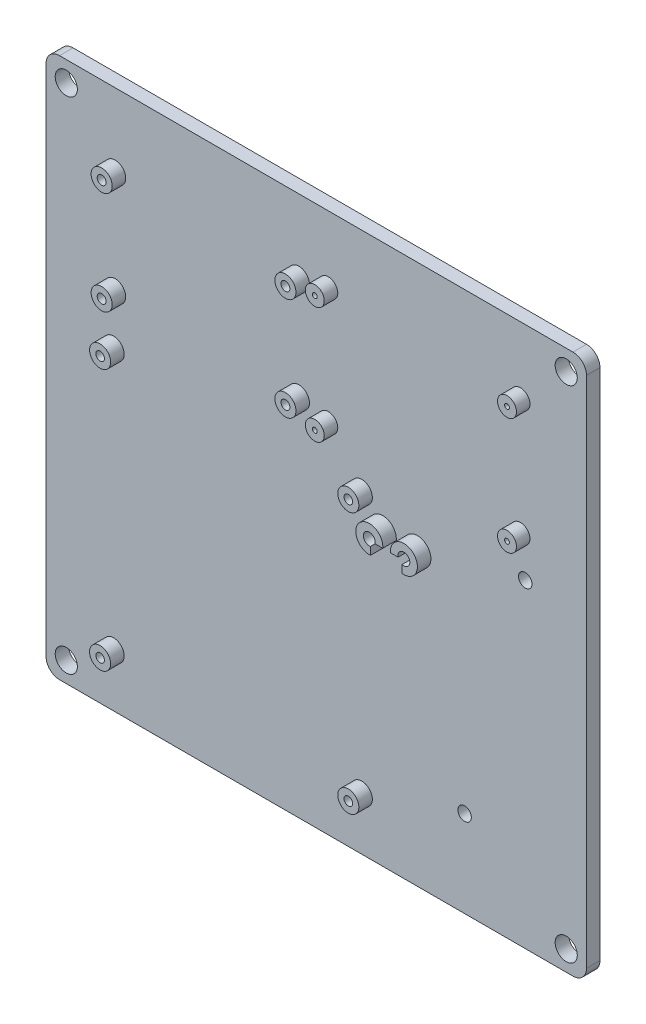
SolidWorks part; units mm, degrees
ref_plane "Alzado" through (0, 0, 0) normal (1, 0, 0) x (0, 1, 0)
ref_plane "Planta" through (0, 0, 0) normal (0, 0, 1) x (0, 1, 0)
ref_plane "Vista lateral" through (0, 0, 0) normal (0, 1, 0) x (-1, 0, 0)
sketch "Croquis1" plane through (0, 0, 0) normal (0, 0, 1) x (0, 1, 0)
  line L1 (-100, -100) -> (100, -100)
  line L2 (-100, -100) -> (-100, 100)
  line L3 (-100, 100) -> (100, 100)
  line L4 (100, -100) -> (100, 100)
  line L5 (-100, -100) -> (100, 100) construction
  line L6 (-100, 100) -> (100, -100) construction
  point P0 (0, 0)
  dimension "D1" = 200
  dimension "D2" = 200
extrude "Saliente-Extruir1" add sketch "Croquis1" along normal blind 5
sketch "Croquis4" plane through (0, 0, 5) normal (0, 0, 1) x (1, 0, 0)
  line L4 (32.4556, 6.9331) -> (36.7578, 6.9331)
  line L5 (36.7578, 6.9331) -> (36.7578, 2.4498)
  line L6 (29.6112, 6.9331) -> (25.086, 6.9331)
  line L7 (25.086, 6.9331) -> (25.086, 2.4245)
  circle A7 centre (4.4664, 32.1842) radius 3.5
  circle A9 centre (4.4664, 32.1842) radius 3.5
  circle A11 centre (4.4664, 32.1842) radius 0.9
  circle A15 centre (4.4664, 32.1842) radius 0.9
  circle A17 centre (75.5865, 75.3643) radius 0.9
  circle A21 centre (75.5865, 75.3643) radius 0.9
  circle A25 centre (75.5865, 75.3643) radius 3.5
  circle A29 centre (75.5865, 75.3643) radius 3.5
  circle A59 centre (-74.9765, 16.2263) radius 1.4
  circle A60 centre (-74.9765, 16.2263) radius 3.9
  circle A61 centre (16.8682, 16.2263) radius 3.9
  circle A62 centre (16.8682, 16.2263) radius 1.4
  circle A63 centre (16.8682, -80.4524) radius 3.9
  circle A64 centre (16.8682, -80.4524) radius 1.4
  circle A65 centre (-74.9765, -80.4524) radius 3.9
  circle A66 centre (-74.9765, -80.4524) radius 1.4
  arc A109 (29.6112, 6.9331) -> (25.086, 2.4245) centre (24.6334, 7.404) ccw
  arc A110 (36.7578, 2.4498) -> (32.4556, 6.9331) centre (37.4334, 7.404) ccw
  circle A257 centre (-6.4085, 72.9217) radius 1.4
  circle A258 centre (-6.4085, 72.9217) radius 3.9
  circle A259 centre (-6.4085, 34.9217) radius 1.4
  circle A260 centre (-6.4085, 34.9217) radius 3.9
  circle A261 centre (-74.4085, 34.9217) radius 1.4
  circle A262 centre (-74.4085, 34.9217) radius 3.9
  circle A532 centre (4.4664, 75.3643) radius 0.9
  circle A534 centre (4.4664, 75.3643) radius 0.9
  circle A536 centre (4.4664, 75.3643) radius 3.5
  circle A538 centre (4.4664, 75.3643) radius 3.5
  circle A540 centre (75.5865, 32.1842) radius 0.9
  circle A542 centre (75.5865, 32.1842) radius 0.9
  circle A544 centre (75.5865, 32.1842) radius 3.5
  circle A783 centre (75.5865, 32.1842) radius 3.5
  circle A792 centre (-74.4085, 72.9217) radius 3.9
  circle A793 centre (-74.4085, 72.9217) radius 3.9
  circle A794 centre (-74.4085, 72.9217) radius 1.4
  circle A795 centre (-74.4085, 72.9217) radius 1.4
  dimension "D11" = 2.8
  dimension "D12" = 7.8
  dimension "D15" = 2
  dimension "D17" = 10
  dimension "D18" = 10
  dimension "D1" = 0
  dimension "D2" = 0
  dimension "D3" = 0
  dimension "D4" = 0
  dimension "D5" = 0
  dimension "D6" = 0
  dimension "D7" = 0
  dimension "D8" = 0
  dimension "D9" = 2
  dimension "D10" = 2
  dimension "D13" = 0
  dimension "D14" = 0
  dimension "D16" = 2
extrude "Saliente-Extruir3" add sketch "Croquis4" along normal blind 5
fillet "Redondeo1" radius 5 4 edges at (-100, 100, 2.5) (-100, -100, 2.5) (100, -100, 2.5) (100, 100, 2.5)
sketch "Croquis5" plane through (0, 0, 5) normal (0, 0, 1) x (0, -1, 0)
  circle A6 centre (-92.5, -92.5) radius 4.1 construction
  circle A7 centre (92.5, -92.5) radius 4.1 construction
  circle A8 centre (92.5, 92.5) radius 4.1 construction
  circle A9 centre (-92.5, 92.5) radius 4.1 construction
  circle A10 centre (-92.5, -92.5) radius 4.1
  circle A11 centre (92.5, -92.5) radius 4.1
  circle A12 centre (92.5, 92.5) radius 4.1
  circle A13 centre (-92.5, 92.5) radius 4.1
extrude "Cortar-Extruir1" cut sketch "Croquis5" against normal blind 5
sketch "Croquis7" plane through (0, 0, 0) normal (0, 0, -1) x (1, 0, 0)
  circle A0 centre (77.3419, -18.0385) radius 2.5 construction
  circle A1 centre (54.8919, 67.9615) radius 2.5 construction
  circle A2 centre (77.3419, -18.0385) radius 2.5
  circle A3 centre (54.8919, 67.9615) radius 2.5
extrude "Cortar-Extruir2" cut sketch "Croquis7" against normal blind 10
sketch "Croquis8" plane through (0, 0, 10) normal (0, 0, 1) x (1, 0, 0)
  circle A0 centre (37.4334, 7.404) radius 2.2
  circle A1 centre (24.6334, 7.404) radius 2.2
  circle A2 centre (-74.9765, -80.4524) radius 1.5875
  circle A3 centre (16.8682, -80.4524) radius 1.5875
  circle A4 centre (16.8682, 16.2263) radius 1.5875
  circle A5 centre (-74.9765, 16.2263) radius 1.5875
  circle A6 centre (-6.4085, 34.9217) radius 1.65
  circle A7 centre (-6.4085, 72.9217) radius 1.65
  circle A8 centre (-74.4085, 72.9217) radius 1.65
  circle A9 centre (-74.4085, 34.9217) radius 1.65
  dimension "D1" = 4.4
  dimension "D2" = 4.4
extrude "Cortar-Extruir3" cut sketch "Croquis8" against normal blind 17
